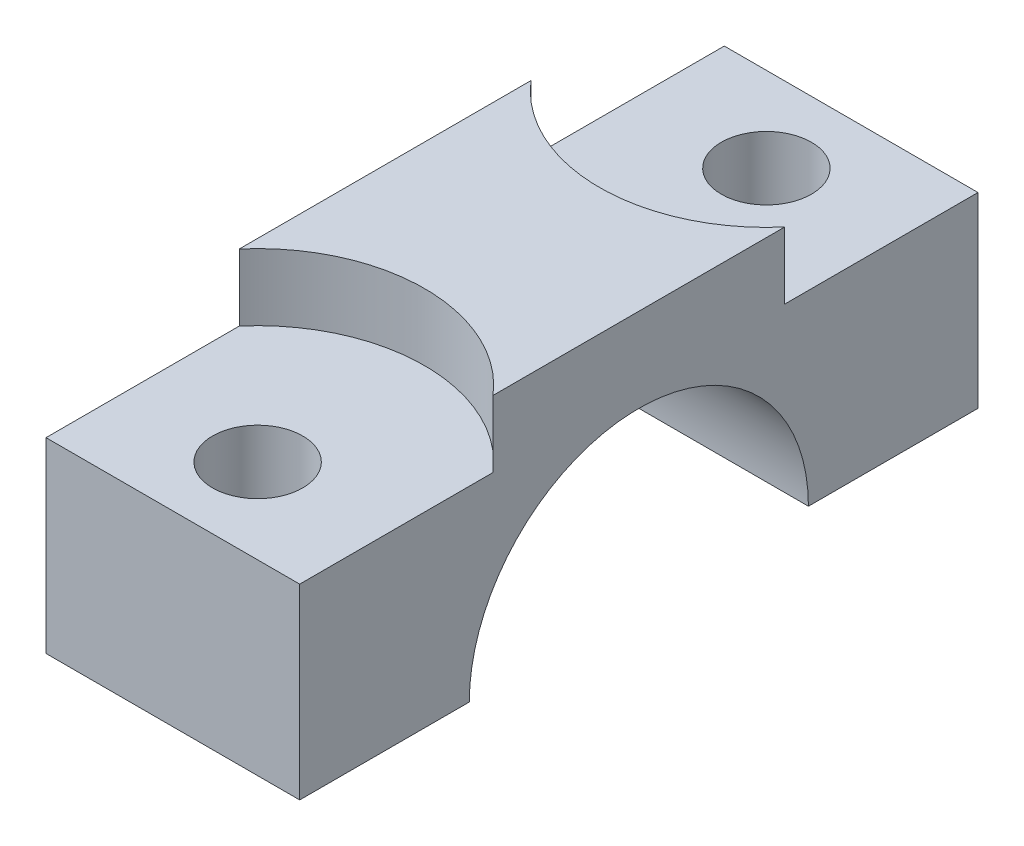
SolidWorks part; units mm, degrees
ref_plane "Front Plane" through (0, 0, 0) normal (0, 0, 1) x (1, 0, 0)
ref_plane "Top Plane" through (0, 0, 0) normal (0, 1, 0) x (1, 0, 0)
ref_plane "Right Plane" through (0, 0, 0) normal (1, 0, 0) x (0, 0, -1)
sketch "Sketch1" plane through (0, 0, 0) normal (1, 0, 0) x (0, 0, -1)
  line L0 (12.7, 0) -> (25.4, 0)
  line L1 (-25.4, 19) -> (25.4, 19)
  line L2 (-25.4, 19) -> (-25.4, 0)
  line L3 (-25.4, 0) -> (-12.7, 0)
  line L4 (25.4, 19) -> (25.4, 0)
  arc A0 (-12.7, 0) -> (12.7, 0) centre (0, 0) cw
  dimension "D3" = 12.7
  dimension "D1" = 50.8
  dimension "D2" = 19
extrude "Boss-Extrude1" add sketch "Sketch1" along normal mid plane 19
sketch "Sketch2" plane through (0, 0, 0) normal (0, -1, 0) x (1, 0, 0)
  line L0 (-9.5, 19.05) -> (9.5, 19.05) construction
  line L1 (-9.5, 25.4) -> (-9.5, 12.7) construction
  line L2 (9.5, 25.4) -> (9.5, 12.7) construction
  line L3 (-9.5, -19.05) -> (9.5, -19.05) construction
  line L4 (-9.5, -12.7) -> (-9.5, -25.4) construction
  line L5 (9.5, -12.7) -> (9.5, -25.4) construction
  point P12 (0, 19.05)
  point P13 (0, -19.05)
hole_wizard "CBORE for M12 Hex Head Cap Screw1" positions "Sketch3" profile "Sketch4" counterbore size "M12" standard "ISO" end condition through all
sketch "Sketch3" plane through (0, 19, 0) normal (0, 1, 0) x (1, 0, 0)
  point P0 (0, 19.05)
  point P3 (0, -19.05)
sketch "Sketch4" plane through (0, 19, -19.05) normal (1, 0, 0) x (0, 0, 1)
  line L0 (0, 0) -> (0, 19)
  line L1 (0, 19) -> (3.375, 19)
  line L3 (3.375, 19) -> (3.375, 5)
  line L4 (3.375, 5) -> (12.5, 5)
  line L5 (12.5, 5) -> (12.5, 0)
  line L7 (12.5, 0) -> (0, 0)
  line L11 (0, -6.35) -> (0, 107.95) construction
  dimension "Thru Hole Dia." = 6.75
  dimension "Thru Hole Depth" = 19
  dimension "C'Bore Dia." = 25
  dimension "C'Bore Depth" = 5
